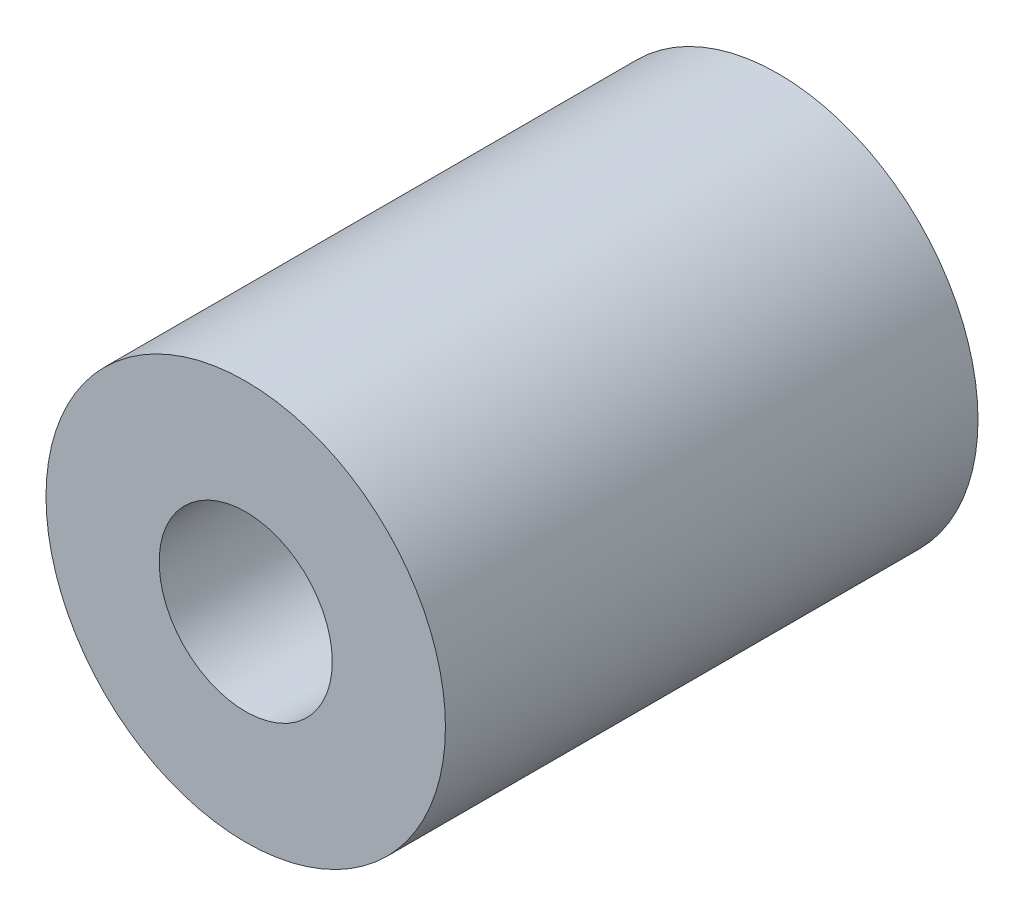
SolidWorks part; units mm, degrees
ref_plane "正面" through (0, 0, 0) normal (0, 0, 1) x (1, 0, 0)
ref_plane "平面" through (0, 0, 0) normal (0, 1, 0) x (1, 0, 0)
ref_plane "右側面" through (0, 0, 0) normal (1, 0, 0) x (0, 0, -1)
sketch "ｽｹｯﾁ1" plane through (0, 0, 0) normal (0, 0, 1) x (1, 0, 0)
  circle A0 centre (0, 0) radius 3
  circle A1 centre (0, 0) radius 1.3
  dimension "D1" = 6
  dimension "D2" = 2.6
extrude "ﾎﾞｽ - 押し出し1" add sketch "ｽｹｯﾁ1" along normal blind 8
